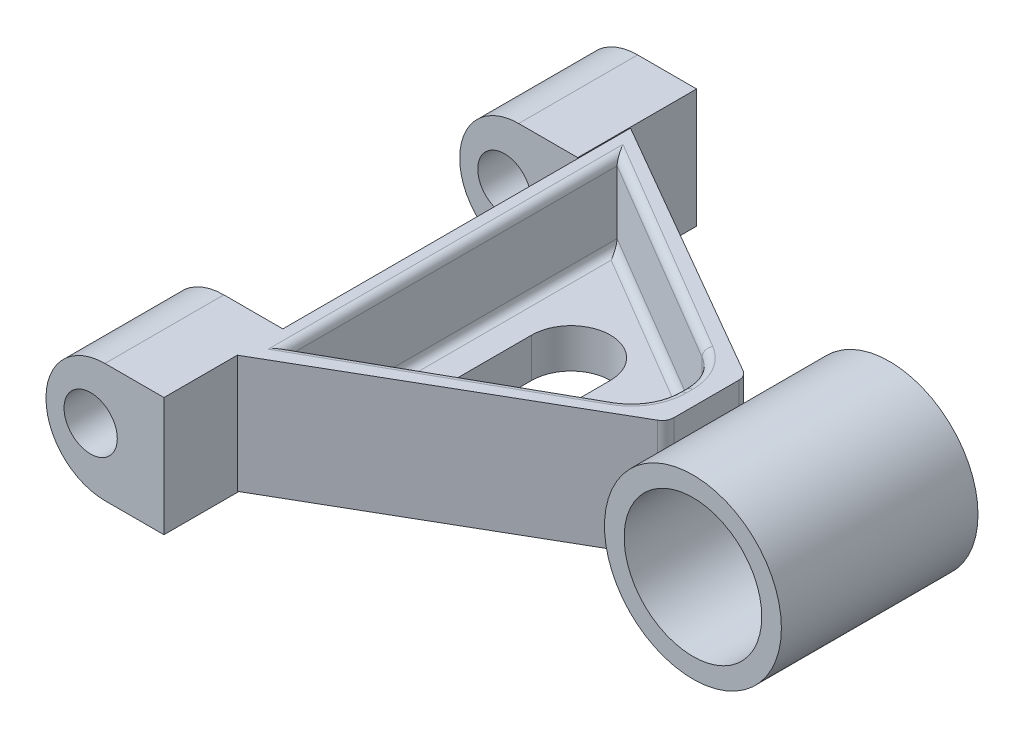
SolidWorks part; units mm, degrees
ref_plane "Front Plane" through (0, 0, 0) normal (0, 0, 1) x (1, 0, 0)
ref_plane "Top Plane" through (0, 0, 0) normal (0, 1, 0) x (1, 0, 0)
ref_plane "Right Plane" through (0, 0, 0) normal (1, 0, 0) x (0, 0, -1)
sketch "Sketch2" plane through (0, 0, 0) normal (0, 1, 0) x (1, 0, 0)
  line L2 (351.9527, -46.0671) -> (351.9527, 55.5329)
  line L4 (351.9527, 55.5329) -> (0, 258.7329)
  line L5 (0, 258.7329) -> (0, -249.2671)
  line L6 (0, -249.2671) -> (351.9527, -46.0671)
  dimension "D1" = 508
  dimension "D2" = 406.4
  dimension "D3" = 406.4
  dimension "D4" = 101.6
extrude "Boss-Extrude1" add sketch "Sketch2" along normal mid plane 152.4
sketch "Sketch3" plane through (0, 76.2, 0) normal (0, 1, 0) x (1, 0, 0)
  line L0 (23.4221, 217.9126) -> (23.4221, -205.2768)
  line L1 (23.4221, -205.2768) -> (291.1103, -54.7466)
  line L2 (322.1907, -1.6116) -> (322.1907, 6.4199)
  line L3 (292.2662, 58.8881) -> (23.4221, 217.9126)
  arc A0 (291.1103, -54.7466) -> (322.1907, -1.6116) centre (261.2307, -1.6116) ccw
  arc A1 (322.1907, 6.4199) -> (292.2662, 58.8881) centre (261.2307, 6.4199) ccw
  dimension "D1" = 60.96
extrude "Cut-Extrude1" cut sketch "Sketch3" against normal blind 101.6
sketch "Sketch4" plane through (0, -25.4, 0) normal (0, 1, 0) x (1, 0, 0)
  line L0 (116.8552, 65.0062) -> (116.8552, -65.0062) construction
  line L1 (167.6552, 65.0062) -> (167.6552, -65.0062)
  line L2 (66.0552, 65.0062) -> (66.0552, -65.0062)
  circle A0 centre (227.8844, 0) radius 38.3119
  arc A1 (167.6552, 65.0062) -> (66.0552, 65.0062) centre (116.8552, 65.0062) ccw
  arc A2 (66.0552, -65.0062) -> (167.6552, -65.0062) centre (116.8552, -65.0062) ccw
  point P4 (116.8552, 0)
  point P9 (110.596, 0)
  dimension "D1" = 50.8
extrude "Cut-Extrude2" cut sketch "Sketch4" against normal blind 50.8
fillet "Fillet1" radius 10.16 12 edges at (157.2662, 76.2, 130.0117) (313.85, 76.2, 32.3903) (322.1907, 76.2, -2.4041) (314.1837, 76.2, -36.6208) (157.2662, -25.4, 130.0117) (313.85, -25.4, 32.3903) (322.1907, -25.4, -2.4041) (314.1837, -25.4, -36.6208) (23.4221, 76.2, -6.3179) (157.8442, 76.2, -138.4003) (23.4221, -25.4, -6.3179) (157.8442, -25.4, -138.4003)
sketch "Sketch5" plane through (0, 0, 0) normal (0, 0, 1) x (1, 0, 0)
  circle A0 centre (466.3584, 0) radius 114.3
  circle A1 centre (466.3584, 0) radius 88.9
  point P2 (461.0932, -7.3917)
  point P3 (478.8208, 0)
  point P4 (468.2633, 0)
  point P6 (467.1812, 0)
  point P7 (466.3584, 0)
  dimension "D1" = 228.6
  dimension "D2" = 177.8
extrude "Boss-Extrude2" add sketch "Sketch5" along normal mid plane 254 separate body
fillet "Fillet2" radius 15.24 2 edges at (351.9527, 0, -55.5329) (351.9527, 0, 46.0671)
sketch "Sketch7" plane through (0, 0, 0) normal (1, 0, 0) x (0, 0, -1)
  line L0 (258.7329, -76.2) -> (-249.2671, -76.2) construction
  line L1 (-190.5, 76.2) -> (-344.0828, 76.2)
  line L2 (-190.5, 76.2) -> (-190.5, -77.3828)
  line L3 (-190.5, -77.3828) -> (-344.0828, -77.3828)
  line L4 (-344.0828, 76.2) -> (-344.0828, -77.3828)
  line L5 (344.0828, 77.3828) -> (190.5, 77.3828)
  line L6 (344.0828, 77.3828) -> (344.0828, -76.2)
  line L7 (344.0828, -76.2) -> (190.5, -76.2)
  line L8 (190.5, 77.3828) -> (190.5, -76.2)
  line L9 (258.7329, 76.2) -> (-249.2671, 76.2) construction
  point P8 (360.6352, -86.8342)
  point P9 (179.0183, -104.288)
  point P10 (187.9069, -103.0103)
  point P11 (187.9069, -76.2)
  point P14 (-183.8571, 76.2)
  point P20 (187.9069, -38.4461)
  dimension "D1" = 381
  dimension "D2" = 190.5
extrude "Boss-Extrude3" add sketch "Sketch7" against normal blind 152.4
sketch "Sketch8" plane through (0, 0, 344.0828) normal (0, 0, 1) x (1, 0, 0)
  circle A0 centre (-94.7166, 0) radius 34.4181
  point P2 (-94.7166, 0)
extrude "Cut-Extrude3" cut sketch "Sketch8" against normal blind 778.002
fillet "Fillet3" radius 76.2 4 edges at (-152.4, 76.2, 267.2914) (-152.4, -77.3828, 267.2914) (-152.4, -76.2, -267.2914) (-152.4, 77.3828, -267.2914)
